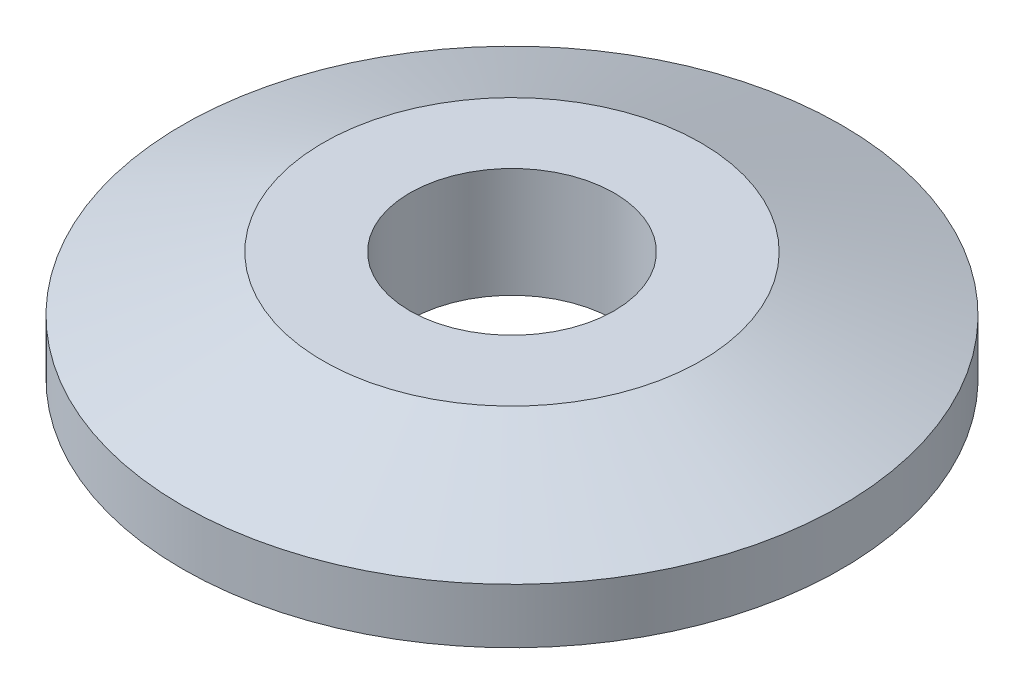
SolidWorks part; units mm, degrees
ref_plane "Front Plane" through (0, 0, 0) normal (0, 0, 1) x (1, 0, 0)
ref_plane "Top Plane" through (0, 0, 0) normal (0, 1, 0) x (1, 0, 0)
ref_plane "Right Plane" through (0, 0, 0) normal (1, 0, 0) x (0, 0, -1)
sketch "Sketch1" plane through (0, 0, 0) normal (0, 1, 0) x (1, 0, 0)
  circle A0 centre (0, 0) radius 15
  dimension "D1" = 30
extrude "Boss-Extrude1" add sketch "Sketch1" along normal blind 5
sketch "Sketch2" plane through (0, 0, 0) normal (0, -1, 0) x (1, 0, 0)
  circle A0 centre (0, 0) radius 8.6
  circle A1 centre (0, 0) radius 15
  circle A2 centre (0, 0) radius 15
  dimension "D2" = 17.2
  dimension "D1" = 0
extrude "Cut-Extrude1" cut sketch "Sketch2" against normal blind 2.5 contours A0
sketch "Sketch4" plane through (0, 0, 0) normal (0, 0, 1) x (1, 0, 0)
  line L0 (15, 5) -> (-15, 5) construction
  line L1 (15, 5) -> (-15, 5) construction
  line L2 (15, 2.5) -> (-15, 2.5) construction
  line L3 (-8.6, 0) -> (8.6, 0) construction
  line L4 (-8.6, 0) -> (8.6, 0) construction
  line L5 (-8.6, 2.5) -> (8.6, 2.5) construction
  line L6 (-8.6, 2.5) -> (8.6, 2.5) construction
  line L7 (15, 2.5) -> (8.6, 5)
  line L8 (0, 2.5) -> (0, 9.4876)
  line L9 (15, 2.5) -> (15, 5)
  line L11 (8.6, 5) -> (15, 5)
  dimension "D1" = 2.5
revolve "Cut-Revolve1" cut sketch "Sketch4" angle 360 about L8
sketch "Sketch5" plane through (0, 5, 0) normal (0, 1, 0) x (1, 0, 0)
  circle A0 centre (0, 0) radius 4.65
  circle A1 centre (0, 0) radius 8.6
  circle A2 centre (0, 0) radius 8.6 construction
  dimension "D2" = 9.3
  dimension "D1" = 0
extrude "Cut-Extrude2" cut sketch "Sketch5" against normal blind 2.5
sketch "Sketch6" plane through (0, 2.5, 0) normal (0, -1, 0) x (1, 0, 0)
  arc A3 (0.6056, 5.9694) -> (-0.6056, -5.9694) centre (0, 0) ccw
  arc A4 (-0.6056, -5.9694) -> (0.6056, 5.9694) centre (0, 0) ccw
  arc A5 (-0.757, -7.4617) -> (0.757, 7.4617) centre (0, 0) ccw
  arc A6 (0.757, 7.4617) -> (-0.757, -7.4617) centre (0, 0) ccw
  arc A7 (-0.757, -7.4617) -> (0.757, 7.4617) centre (0, 0) ccw
  arc A8 (0.757, 7.4617) -> (-0.757, -7.4617) centre (0, 0) ccw
  dimension "D1" = 0.5
  dimension "D2" = 1.5
extrude "Cut-Extrude3" cut sketch "Sketch6" against normal blind 1
sketch "Sketch7" plane through (0, 2.5, 0) normal (0, -1, 0) x (1, 0, 0)
  circle A0 centre (0, 0) radius 4.65 construction
  circle A1 centre (0, 0) radius 6
  circle A2 centre (0, 0) radius 6
  circle A3 centre (0, 0) radius 4.65
  dimension "D1" = 0
extrude "Boss-Extrude2" add sketch "Sketch7" along normal up to surface (2.5 mm away) up to face at (0, 0, -8.6)
